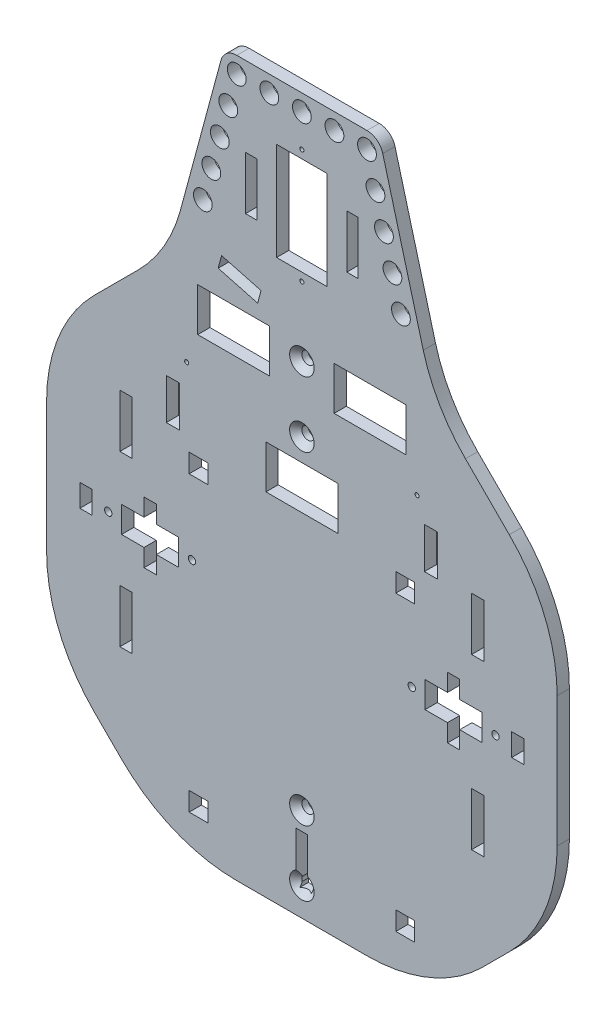
SolidWorks part; units mm, degrees
other "Popis1"
sketch "Skica4" plane through (-62.5, 107.5, 3) normal (-0.0791, 0.0312, 0.9964) x (0.9969, 0.0058, 0.079)
sketch "Skica5" plane through (-62.5, 107.5, 3) normal (-0.0791, 0.0312, 0.9964) x (0.9969, 0.0058, 0.079)
sketch "Skica6" plane through (-62.5, 112.5, 3) normal (-0.0791, 0.0312, 0.9964) x (0.9969, 0.0058, 0.079)
sketch "Skica7" plane through (-62.5, 112.5, 3) normal (-0.0791, 0.0312, 0.9964) x (0.9969, 0.0058, 0.079)
ref_plane "Přední rovina" through (0, 0, 0) normal (0, 0, 1) x (1, 0, 0)
ref_plane "Horní rovina" through (0, 0, 0) normal (0, 1, 0) x (1, 0, 0)
ref_plane "Pravá rovina" through (0, 0, 0) normal (1, 0, 0) x (0, 0, -1)
sketch "Skica1" plane through (0, 0, 0) normal (0, 0, 1) x (1, 0, 0)
  line L0 (-334.3708, 0) -> (16384.1714, 0) construction
  line L1 (0, -334.3708) -> (0, 16384.1714) construction
  line L2 (-44.3956, 7.5) -> (-44.3956, -7.5) construction
  line L3 (-62.5, -62.5) -> (62.5, -62.5) construction
  line L4 (-62.5, -62.5) -> (-62.5, 62.5) construction
  line L5 (-62.5, 62.5) -> (62.5, 62.5) construction
  line L6 (62.5, -62.5) -> (62.5, 62.5) construction
  line L7 (-62.5, -62.5) -> (62.5, 62.5) construction
  line L8 (-62.5, 62.5) -> (62.5, -62.5) construction
  line L9 (-44.3956, 7.5) -> (-61.3, 7.5) construction
  line L10 (-41.5478, 0) -> (-41.5478, 14.2) construction
  line L11 (-44.1478, 3.2) -> (-38.6478, 3.2)
  line L13 (-44.5478, 27.2) -> (-41.5478, 27.2)
  line L14 (-44.5478, 27.2) -> (-44.5478, 14.2)
  line L15 (-44.5478, 14.2) -> (-41.5478, 14.2)
  line L16 (-41.5478, 27.2) -> (-41.5478, 14.2)
  line L20 (-54.3478, 2.75) -> (-51.3478, 2.75)
  line L21 (-54.3478, 2.75) -> (-54.3478, -2.75)
  line L22 (-54.3478, -2.75) -> (-51.3478, -2.75)
  line L23 (-51.3478, 2.75) -> (-51.3478, -2.75)
  line L24 (-54.3478, 2.75) -> (-51.3478, -2.75) construction
  line L25 (-54.3478, -2.75) -> (-51.3478, 2.75) construction
  line L26 (-44.1478, 3.2) -> (-30.1478, 3.2) construction
  line L27 (-44.1478, 3.2) -> (-44.1478, -3.2)
  line L28 (-44.1478, -3.2) -> (-30.1478, -3.2) construction
  line L29 (-30.1478, 3.2) -> (-30.1478, -3.2)
  line L30 (-44.1478, 3.2) -> (-30.1478, -3.2) construction
  line L31 (-44.1478, -3.2) -> (-30.1478, 3.2) construction
  line L32 (-38.6478, -7.5) -> (-35.6478, -7.5)
  line L33 (-38.6478, -7.5) -> (-38.6478, 7.5) construction
  line L34 (-38.6478, 7.5) -> (-35.6478, 7.5)
  line L35 (-35.6478, -7.5) -> (-35.6478, 7.5) construction
  line L36 (-38.6478, -7.5) -> (-35.6478, 7.5) construction
  line L37 (-38.6478, 7.5) -> (-35.6478, -7.5) construction
  line L38 (-38.6478, 3.2) -> (-38.6478, 7.5)
  line L39 (-35.6478, 7.5) -> (-35.6478, 3.2)
  line L40 (-35.6478, 3.2) -> (-30.1478, 3.2)
  line L41 (-30.1478, -3.2) -> (-35.6478, -3.2)
  line L42 (-35.6478, -3.2) -> (-35.6478, -7.5)
  line L43 (-38.6478, -7.5) -> (-38.6478, -3.2)
  line L44 (-38.6478, -3.2) -> (-44.1478, -3.2)
  line L45 (-41.5478, -27.2) -> (-41.5478, -14.2)
  line L46 (-44.5478, -27.2) -> (-41.5478, -27.2)
  line L47 (-44.5478, -27.2) -> (-44.5478, -14.2)
  line L48 (-44.5478, -14.2) -> (-41.5478, -14.2)
  line L49 (-62.5, -32.5) -> (-62.5, 32.5)
  line L50 (-62.5, 32.5) -> (-32.5, 62.5)
  line L51 (-62.5, -32.5) -> (-32.5, -62.5)
  line L52 (-32.5, -62.5) -> (32.5, -62.5)
  line L54 (38.6478, -7.5) -> (35.6478, -7.5)
  line L55 (38.6478, -7.5) -> (38.6478, -3.2)
  line L56 (35.6478, -3.2) -> (35.6478, -7.5)
  line L57 (30.1478, -3.2) -> (35.6478, -3.2)
  line L58 (38.6478, -3.2) -> (44.1478, -3.2)
  line L59 (30.1478, 3.2) -> (30.1478, -3.2)
  line L60 (35.6478, 3.2) -> (30.1478, 3.2)
  line L61 (38.6478, 7.5) -> (35.6478, 7.5)
  line L62 (35.6478, 7.5) -> (35.6478, 3.2)
  line L63 (38.6478, 3.2) -> (38.6478, 7.5)
  line L64 (44.1478, 3.2) -> (44.1478, -3.2)
  line L65 (44.1478, 3.2) -> (38.6478, 3.2)
  line L66 (51.3478, 2.75) -> (51.3478, -2.75)
  line L67 (54.3478, -2.75) -> (51.3478, -2.75)
  line L68 (54.3478, 2.75) -> (54.3478, -2.75)
  line L69 (54.3478, 2.75) -> (51.3478, 2.75)
  line L70 (41.5478, 27.2) -> (41.5478, 14.2)
  line L71 (44.5478, 14.2) -> (41.5478, 14.2)
  line L72 (44.5478, 27.2) -> (44.5478, 14.2)
  line L73 (44.5478, 27.2) -> (41.5478, 27.2)
  line L74 (44.5478, -14.2) -> (41.5478, -14.2)
  line L75 (44.5478, -27.2) -> (44.5478, -14.2)
  line L76 (44.5478, -27.2) -> (41.5478, -27.2)
  line L77 (41.5478, -27.2) -> (41.5478, -14.2)
  line L78 (62.5, -32.5) -> (32.5, -62.5)
  line L79 (62.5, -32.5) -> (62.5, 32.5)
  line L80 (62.5, 32.5) -> (32.5, 62.5)
  line L81 (25.5, 59.1) -> (25.5, 48.5)
  line L82 (-8.8, 34.1) -> (8.8, 34.1)
  line L83 (-8.8, 34.1) -> (-8.8, 23.5)
  line L84 (-8.8, 23.5) -> (8.8, 23.5)
  line L85 (8.8, 34.1) -> (8.8, 23.5)
  line L86 (-8.8, 34.1) -> (8.8, 23.5) construction
  line L87 (-8.8, 23.5) -> (8.8, 34.1) construction
  line L88 (-25.5, 59.1) -> (-7.9, 59.1)
  line L89 (-25.5, 59.1) -> (-25.5, 48.5)
  line L90 (-25.5, 48.5) -> (-7.9, 48.5)
  line L91 (-7.9, 59.1) -> (-7.9, 48.5)
  line L92 (7.9, 59.1) -> (7.9, 48.5)
  line L93 (25.5, 48.5) -> (7.9, 48.5)
  line L94 (25.5, 59.1) -> (7.9, 59.1)
  line L95 (-6.2, 74.5) -> (-6.2, 98.5)
  line L96 (-6.2, 98.5) -> (6.2, 98.5)
  line L97 (6.2, 98.5) -> (6.2, 74.5)
  line L98 (6.2, 74.5) -> (-6.2, 74.5)
  line L99 (-11, 93) -> (-11, 80)
  line L100 (-11, 80) -> (-13.8, 80)
  line L101 (-13.8, 80) -> (-13.8, 93)
  line L102 (-13.8, 93) -> (-11, 93)
  line L107 (-20.4875, 65.0882) -> (-10.8282, 62.5)
  line L108 (-10.8282, 62.5) -> (-10, 65.591)
  line L109 (-10, 65.591) -> (-19.6593, 68.1792)
  line L110 (-19.6593, 68.1792) -> (-20.4875, 65.0882)
  line L111 (-6.2, 86.5) -> (6.2, 86.5) construction
  line L112 (-6.2, 86.5) -> (-11, 86.5) construction
  line L113 (11, 80) -> (13.8, 80)
  line L114 (11, 93) -> (11, 80)
  line L115 (13.8, 93) -> (11, 93)
  line L116 (13.8, 80) -> (13.8, 93)
  line L117 (30, 26) -> (33.2, 26)
  line L118 (-30, 36) -> (-33.2, 36)
  line L119 (-30, 36) -> (-30, 26)
  line L120 (-30, 26) -> (-33.2, 26)
  line L121 (-33.2, 36) -> (-33.2, 26)
  line L122 (33.2, 36) -> (33.2, 26)
  line L123 (30, 36) -> (33.2, 36)
  line L124 (30, 36) -> (30, 26)
  line L125 (-32.5, 62.5) -> (-19.0034, 112.5)
  line L126 (-19.0034, 112.5) -> (19.0034, 112.5)
  line L129 (0, 108.5) -> (7.97, 108.5) construction
  line L137 (32.5, 62.5) -> (19.0034, 112.5)
  line L138 (-15.94, 108.5) -> (-28.3568, 62.5) construction
  line L140 (-25.3, -51.5) -> (25.3, -51.5) construction
  line L141 (-25.3, -51.5) -> (-25.3, 20.23) construction
  line L142 (-25.3, 20.23) -> (25.3, 20.23) construction
  line L143 (25.3, -51.5) -> (25.3, 20.23) construction
  line L144 (-25.3, -51.5) -> (25.3, 20.23) construction
  line L145 (-25.3, 20.23) -> (25.3, -51.5) construction
  line L146 (-25.3, -15.635) -> (25.3, -15.635) construction
  line L147 (23, 22.53) -> (27.6, 22.53)
  line L148 (23, 22.53) -> (23, 17.93)
  line L149 (23, 17.93) -> (27.6, 17.93)
  line L150 (27.6, 22.53) -> (27.6, 17.93)
  line L151 (23, 22.53) -> (27.6, 17.93) construction
  line L152 (23, 17.93) -> (27.6, 22.53) construction
  line L153 (23, -49.2) -> (27.6, -49.2)
  line L154 (27.6, -53.8) -> (27.6, -49.2)
  line L155 (23, -53.8) -> (27.6, -53.8)
  line L156 (23, -53.8) -> (23, -49.2)
  line L157 (-23, -53.8) -> (-27.6, -53.8)
  line L158 (-23, -53.8) -> (-23, -49.2)
  line L159 (-27.6, -53.8) -> (-27.6, -49.2)
  line L160 (-23, -49.2) -> (-27.6, -49.2)
  line L161 (-23, 22.53) -> (-23, 17.93)
  line L162 (-23, 22.53) -> (-27.6, 22.53)
  line L163 (-27.6, 22.53) -> (-27.6, 17.93)
  line L164 (-23, 17.93) -> (-27.6, 17.93)
  line L165 (37.1478, 7.5) -> (37.1478, -7.5) construction
  circle A0 centre (-52.8478, 0) radius 11.3 construction
  circle A1 centre (0, 100.5) radius 0.5
  circle A3 centre (0, 72.5) radius 0.5
  circle A4 centre (0, 108.5) radius 2.3
  circle A5 centre (7.97, 108.5) radius 2.3
  circle A6 centre (15.94, 108.5) radius 2.3
  circle A7 centre (-15.94, 108.5) radius 2.3
  circle A8 centre (-7.97, 108.5) radius 2.3
  circle A9 centre (-15.94, 108.5) radius 2.3 construction
  circle A10 centre (-18.017, 100.8054) radius 2.3
  circle A11 centre (-20.094, 93.1108) radius 2.3
  circle A12 centre (-22.171, 85.4162) radius 2.3
  circle A13 centre (-24.2481, 77.7216) radius 2.3
  circle A14 centre (24.2481, 77.7216) radius 2.3
  circle A15 centre (22.171, 85.4162) radius 2.3
  circle A16 centre (20.094, 93.1108) radius 2.3
  circle A17 centre (18.017, 100.8054) radius 2.3
  circle A18 centre (47.3978, 0) radius 0.9
  circle A19 centre (26.8978, 0) radius 0.9
  circle A20 centre (-47.3978, 0) radius 0.9
  circle A21 centre (-26.8978, 0) radius 0.9
  point P4 (0, 0)
  point P15 (-52.8478, 0)
  point P17 (-37.1478, 0)
  point P27 (-37.1478, 0)
  point P46 (52.8478, 0)
  point P48 (0, 28.8)
  point P49 (0, -62.5)
  point P78 (0, 62.5)
  point P138 (0, 112.5)
  point P149 (-15.94, 108.5)
  point P156 (0, -15.635)
  dimension "D3" = 13
  dimension "D6" = 22.6
  dimension "D30" = 1
  dimension "D40" = 4.6
  dimension "D44" = 4
  dimension "D53" = 1.8
  dimension "D1" = 125
  dimension "D2" = 125
  dimension "D4" = 3
  dimension "D5" = 14.2
  dimension "D7" = 15
  dimension "D8" = 1.2
  dimension "D9" = 3
  dimension "D10" = 5.5
  dimension "D11" = 6.8
  dimension "D12" = 14
  dimension "D13" = 6.4
  dimension "D14" = 3
  dimension "D15" = 15
  dimension "D17" = 65
  dimension "D18" = 45
  dimension "D19" = 86
  dimension "D20" = 17.6
  dimension "D21" = 10.6
  dimension "D22" = 7.9
  dimension "D23" = 14.4
  dimension "D24" = 12.4
  dimension "D25" = 24
  dimension "D26" = 13
  dimension "D27" = 2.8
  dimension "D28" = 11
  dimension "D29" = 12
  dimension "D31" = 2
  dimension "D32" = 10
  dimension "D33" = 3.2
  dimension "D34" = 10
  dimension "D35" = 15
  dimension "D36" = 3.2
  dimension "D37" = 10
  dimension "D38" = 30
  dimension "D39" = 26
  dimension "D42" = 7.97
  dimension "D43" = 4
  dimension "D45" = 8
  dimension "D46" = 74.894
  dimension "D47" = 2
  dimension "D48" = 71.73
  dimension "D49" = 50.6
  dimension "D50" = 11
  dimension "D51" = 4.6
  dimension "D52" = 10.25
  dimension "D54" = 14.2
  dimension "D41" = 3
extrude "Přidat vysunutím1" add sketch "Skica1" along normal blind 3
sketch "Skica2" plane through (0, 0, 0) normal (0, 0, 1) x (1, 0, 0)
  line L0 (0, -1000) -> (0, 49000) construction
  line L1 (-1000, 0) -> (49000, 0) construction
  line L2 (8.8, 34.1) -> (-8.8, 34.1) construction
  circle A0 centre (0, 39.6) radius 1.5
  circle A1 centre (0, 55.6) radius 1.5
  circle A2 centre (0, -55.6) radius 1.5
  circle A3 centre (0, -39.6) radius 1.5
  dimension "D3" = 3
  dimension "D1" = 5.5
  dimension "D2" = 16
extrude "Odebrat vysunutím1" cut sketch "Skica2" along normal up to surface (3 mm away) up to face at (-25.3, -51.5, 3)
chamfer "Zkosení1" distance 1.5 angle 45 4 edges at (-1.5, -55.6, 3) (-1.5, -39.6, 3) (-1.5, 39.6, 3) (-1.5, 55.6, 3)
fillet "Zaoblit1" radius 40 8 edges at (-62.5, -32.5, 1.5) (-32.5, -62.5, 1.5) (32.5, -62.5, 1.5) (62.5, -32.5, 1.5) (62.5, 32.5, 1.5) (-62.5, 32.5, 1.5) (32.5, 62.5, 1.5) (-32.5, 62.5, 1.5)
fillet "Zaoblit2" radius 4 2 edges at (19.0034, 112.5, 1.5) (-19.0034, 112.5, 1.5)
sketch "Skica3" plane through (0, 0, 3) normal (0, 0, 1) x (1, 0, 0)
  line L0 (0, -965.9) -> (0, 49034.1) construction
  line L1 (8.8, 34.1) -> (-8.8, 34.1) construction
  line L2 (-11, 93) -> (-13.8, 93) construction
  line L3 (-1.4, -44.1) -> (1.4, -44.1)
  line L4 (-1.4, -44.1) -> (-1.4, -57.1)
  line L5 (-1.4, -57.1) -> (1.4, -57.1)
  line L6 (1.4, -44.1) -> (1.4, -57.1)
  line L7 (-13.8, 93) -> (-13.8, 80) construction
  circle A0 centre (-28.2, 41.3) radius 0.5
  circle A1 centre (28.2, 41.3) radius 0.5
  circle A2 centre (0, -55.6) radius 1.5 construction
  point P5 (0, 34.1)
  dimension "D1" = 1
  dimension "D2" = 28.2
  dimension "D3" = 7.2
extrude "Odebrat vysunutím2" cut sketch "Skica3" against normal through all
